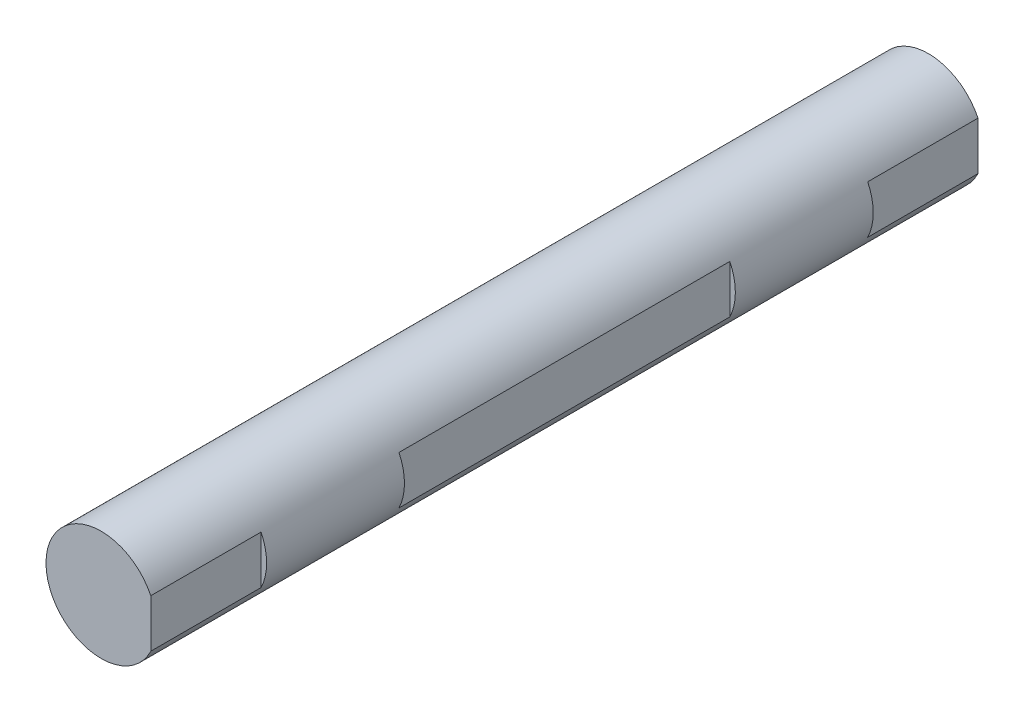
SolidWorks part; units mm, degrees
material "AISI 304"
ref_plane "前视基准面" through (0, 0, 0) normal (0, 0, 1) x (1, 0, 0)
ref_plane "上视基准面" through (0, 0, 0) normal (0, 1, 0) x (1, 0, 0)
ref_plane "右视基准面" through (0, 0, 0) normal (1, 0, 0) x (0, 0, -1)
sketch "草图1" plane through (0, 0, 0) normal (0, 0, 1) x (1, 0, 0)
  circle A0 centre (0, 0) radius 5
  dimension "D1" = 10
extrude "凸台-拉伸1" add sketch "草图1" along normal blind 75
ref_plane "基准面1" through (5, 0, 0) normal (1, 0, 0) x (0, 0, -1)
sketch "草图2" plane through (5, 0, 0) normal (1, 0, 0) x (0, 0, -1)
  line L0 (-37.5, 5) -> (-37.5, -17.7036) construction
  line L1 (0, 5) -> (-75, 5) construction
  line L2 (-75, -5) -> (0, -5) construction
  line L3 (-52.5, 5) -> (-22.5, 5)
  line L4 (-37.5, 5) -> (-37.5, -5)
  line L5 (-52.5, -5) -> (-22.5, -5)
  line L6 (-22.5, 5) -> (-22.5, -5)
  line L7 (-75, 5) -> (-75, -5)
  line L8 (-10, 5) -> (0, 5)
  line L9 (-10, 5) -> (-10, -5)
  line L10 (-10, -5) -> (0, -5)
  line L11 (0, 5) -> (0, -5)
  line L12 (-65, -5) -> (-75, -5)
  line L13 (-65, 5) -> (-65, -5)
  line L14 (-65, 5) -> (-75, 5)
  line L15 (-52.5, 5) -> (-52.5, -5)
  dimension "D1" = 15
  dimension "D2" = 10
extrude "切除-拉伸1" cut sketch "草图2" against normal blind 0.5 contours L7 L12 L13 L14 | L15 L5 L6 L3 | L10 L11 L8 L9
